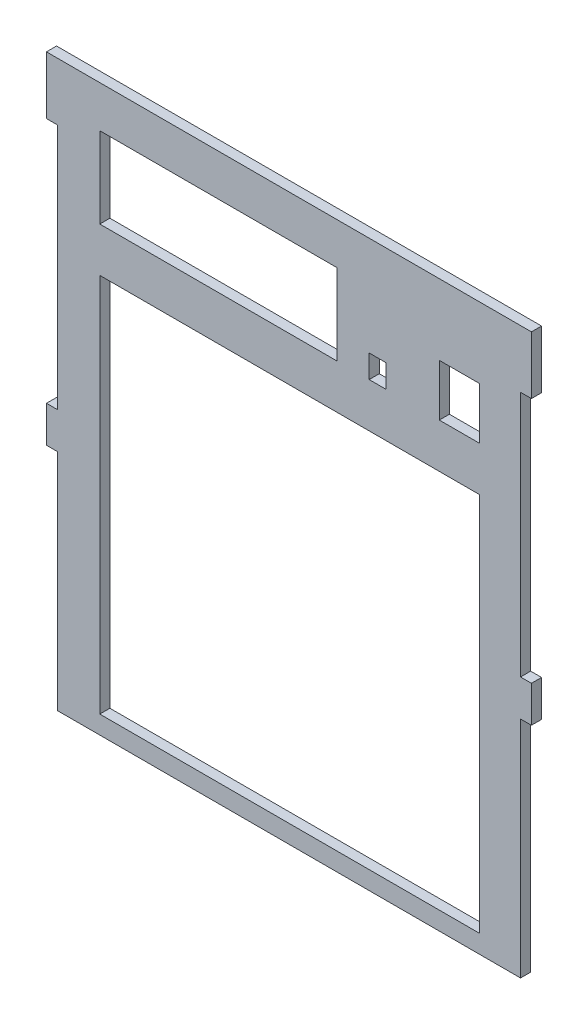
SolidWorks part; units mm, degrees
ref_plane "Front Plane" through (0, 0, 0) normal (0, 0, 1) x (1, 0, 0)
ref_plane "Top Plane" through (0, 0, 0) normal (0, 1, 0) x (1, 0, 0)
ref_plane "Right Plane" through (0, 0, 0) normal (1, 0, 0) x (0, 0, -1)
sketch "Sketch1" plane through (0, 0, 0) normal (0, 0, 1) x (1, 0, 0)
  line L1 (0, 0) -> (152.4, 0)
  line L2 (0, 0) -> (0, 241.3)
  line L3 (0, 241.3) -> (152.4, 241.3)
  line L4 (152.4, 0) -> (152.4, 241.3)
  dimension "D1" = 241.3
  dimension "D2" = 152.4
extrude "Boss-Extrude1" add sketch "Sketch1" along normal blind 3.175
sketch "Sketch2" plane through (0, 0, 3.175) normal (0, 0, 1) x (1, 0, 0)
  line L0 (152.4, 0) -> (152.4, 241.3) construction
  line L1 (152.4, 223.139) -> (148.971, 223.139)
  line L2 (152.4, 223.139) -> (152.4, 54.991)
  line L3 (152.4, 54.991) -> (148.971, 54.991)
  line L4 (148.971, 223.139) -> (148.971, 54.991)
  line L5 (0, 241.3) -> (0, 0) construction
  line L6 (0, 223.139) -> (3.429, 223.139)
  line L7 (0, 223.139) -> (0, 54.991)
  line L8 (0, 54.991) -> (3.429, 54.991)
  line L9 (3.429, 223.139) -> (3.429, 54.991)
  line L10 (152.4, 241.3) -> (0, 241.3) construction
  line L12 (152.4, 0) -> (148.971, 0)
  line L13 (152.4, 0) -> (152.4, 40.386)
  line L14 (152.4, 40.386) -> (148.971, 40.386)
  line L15 (148.971, 0) -> (148.971, 40.386)
  line L16 (0, 0) -> (3.429, 0)
  line L17 (0, 0) -> (0, 40.386)
  line L18 (0, 40.386) -> (3.429, 40.386)
  line L19 (3.429, 0) -> (3.429, 40.386)
  dimension "D1" = 18.161
  dimension "D2" = 14.605
  dimension "D3" = 3.429
  dimension "D4" = 40.386
extrude "Cut-Extrude1" cut sketch "Sketch2" against normal through all
sketch "Sketch3" plane through (0, 0, 3.175) normal (0, 0, 1) x (1, 0, 0)
  line L0 (3.429, 57.15) -> (148.971, 57.15) construction
  line L1 (3.429, 0) -> (148.971, 0) construction
  line L2 (148.971, 223.139) -> (148.971, 54.991) construction
  line L3 (3.429, 54.991) -> (3.429, 223.139) construction
  line L4 (128.016, 57.15) -> (140.716, 57.15)
  line L5 (140.716, 57.15) -> (140.716, 44.45)
  line L6 (140.716, 44.45) -> (128.016, 57.15)
  line L7 (125.7709, 57.15) -> (140.716, 42.2049) construction
  line L8 (125.7709, 42.2049) -> (138.4709, 42.2049)
  line L9 (125.7709, 54.9049) -> (125.7709, 42.2049)
  line L10 (138.4709, 42.2049) -> (125.7709, 54.9049)
  line L11 (108.966, 57.15) -> (121.666, 57.15)
  line L12 (121.666, 44.45) -> (108.966, 57.15)
  line L13 (119.4209, 42.2049) -> (106.7209, 54.9049)
  line L14 (106.7209, 54.9049) -> (106.7209, 42.2049)
  line L15 (106.7209, 42.2049) -> (119.4209, 42.2049)
  line L16 (121.666, 57.15) -> (121.666, 44.45)
  line L17 (89.916, 57.15) -> (102.616, 57.15)
  line L18 (102.616, 44.45) -> (89.916, 57.15)
  line L19 (100.3709, 42.2049) -> (87.6709, 54.9049)
  line L20 (87.6709, 54.9049) -> (87.6709, 42.2049)
  line L21 (87.6709, 42.2049) -> (100.3709, 42.2049)
  line L22 (102.616, 57.15) -> (102.616, 44.45)
  line L23 (70.866, 57.15) -> (83.566, 57.15)
  line L24 (83.566, 44.45) -> (70.866, 57.15)
  line L25 (81.3209, 42.2049) -> (68.6209, 54.9049)
  line L26 (68.6209, 54.9049) -> (68.6209, 42.2049)
  line L27 (68.6209, 42.2049) -> (81.3209, 42.2049)
  line L28 (83.566, 57.15) -> (83.566, 44.45)
  line L29 (51.816, 57.15) -> (64.516, 57.15)
  line L30 (64.516, 44.45) -> (51.816, 57.15)
  line L31 (62.2709, 42.2049) -> (49.5709, 54.9049)
  line L32 (49.5709, 54.9049) -> (49.5709, 42.2049)
  line L33 (49.5709, 42.2049) -> (62.2709, 42.2049)
  line L34 (64.516, 57.15) -> (64.516, 44.45)
  line L35 (32.766, 57.15) -> (45.466, 57.15)
  line L36 (45.466, 44.45) -> (32.766, 57.15)
  line L37 (43.2209, 42.2049) -> (30.5209, 54.9049)
  line L38 (30.5209, 54.9049) -> (30.5209, 42.2049)
  line L39 (30.5209, 42.2049) -> (43.2209, 42.2049)
  line L40 (45.466, 57.15) -> (45.466, 44.45)
  line L41 (13.716, 57.15) -> (26.416, 57.15)
  line L42 (26.416, 44.45) -> (13.716, 57.15)
  line L43 (24.1709, 42.2049) -> (11.4709, 54.9049)
  line L44 (11.4709, 54.9049) -> (11.4709, 42.2049)
  line L45 (11.4709, 42.2049) -> (24.1709, 42.2049)
  line L46 (26.416, 57.15) -> (26.416, 44.45)
  line L47 (128.016, 38.1) -> (140.716, 38.1)
  line L48 (16.764, 188.849) -> (136.144, 188.849)
  line L49 (16.764, 188.849) -> (16.764, 69.469)
  line L50 (16.764, 69.469) -> (136.144, 69.469)
  line L51 (136.144, 188.849) -> (136.144, 69.469)
  line L52 (140.716, 38.1) -> (140.716, 25.4)
  line L53 (140.716, 25.4) -> (128.016, 38.1)
  line L54 (125.7709, 23.1549) -> (138.4709, 23.1549)
  line L55 (125.7709, 35.8549) -> (125.7709, 23.1549)
  line L56 (138.4709, 23.1549) -> (125.7709, 35.8549)
  line L57 (108.966, 38.1) -> (121.666, 38.1)
  line L58 (121.666, 25.4) -> (108.966, 38.1)
  line L59 (119.4209, 23.1549) -> (106.7209, 35.8549)
  line L60 (106.7209, 35.8549) -> (106.7209, 23.1549)
  line L61 (106.7209, 23.1549) -> (119.4209, 23.1549)
  line L62 (121.666, 38.1) -> (121.666, 25.4)
  line L63 (89.916, 38.1) -> (102.616, 38.1)
  line L64 (102.616, 25.4) -> (89.916, 38.1)
  line L65 (100.3709, 23.1549) -> (87.6709, 35.8549)
  line L66 (87.6709, 35.8549) -> (87.6709, 23.1549)
  line L67 (87.6709, 23.1549) -> (100.3709, 23.1549)
  line L68 (102.616, 38.1) -> (102.616, 25.4)
  line L69 (70.866, 38.1) -> (83.566, 38.1)
  line L70 (83.566, 25.4) -> (70.866, 38.1)
  line L71 (81.3209, 23.1549) -> (68.6209, 35.8549)
  line L72 (68.6209, 35.8549) -> (68.6209, 23.1549)
  line L73 (68.6209, 23.1549) -> (81.3209, 23.1549)
  line L74 (83.566, 38.1) -> (83.566, 25.4)
  line L75 (51.816, 38.1) -> (64.516, 38.1)
  line L76 (64.516, 25.4) -> (51.816, 38.1)
  line L77 (62.2709, 23.1549) -> (49.5709, 35.8549)
  line L78 (49.5709, 35.8549) -> (49.5709, 23.1549)
  line L79 (49.5709, 23.1549) -> (62.2709, 23.1549)
  line L80 (64.516, 38.1) -> (64.516, 25.4)
  line L81 (32.766, 38.1) -> (45.466, 38.1)
  line L82 (45.466, 25.4) -> (32.766, 38.1)
  line L83 (43.2209, 23.1549) -> (30.5209, 35.8549)
  line L84 (30.5209, 35.8549) -> (30.5209, 23.1549)
  line L85 (30.5209, 23.1549) -> (43.2209, 23.1549)
  line L86 (45.466, 38.1) -> (45.466, 25.4)
  line L87 (13.716, 38.1) -> (26.416, 38.1)
  line L88 (26.416, 25.4) -> (13.716, 38.1)
  line L89 (24.1709, 23.1549) -> (11.4709, 35.8549)
  line L90 (11.4709, 35.8549) -> (11.4709, 23.1549)
  line L91 (11.4709, 23.1549) -> (24.1709, 23.1549)
  line L92 (26.416, 38.1) -> (26.416, 25.4)
  line L93 (128.016, 19.05) -> (140.716, 19.05)
  line L94 (140.716, 19.05) -> (140.716, 6.35)
  line L95 (140.716, 6.35) -> (128.016, 19.05)
  line L96 (125.7709, 4.1049) -> (138.4709, 4.1049)
  line L97 (125.7709, 16.8049) -> (125.7709, 4.1049)
  line L98 (138.4709, 4.1049) -> (125.7709, 16.8049)
  line L99 (108.966, 19.05) -> (121.666, 19.05)
  line L100 (121.666, 6.35) -> (108.966, 19.05)
  line L101 (119.4209, 4.1049) -> (106.7209, 16.8049)
  line L102 (106.7209, 16.8049) -> (106.7209, 4.1049)
  line L103 (106.7209, 4.1049) -> (119.4209, 4.1049)
  line L104 (121.666, 19.05) -> (121.666, 6.35)
  line L105 (89.916, 19.05) -> (102.616, 19.05)
  line L106 (102.616, 6.35) -> (89.916, 19.05)
  line L107 (100.3709, 4.1049) -> (87.6709, 16.8049)
  line L108 (87.6709, 16.8049) -> (87.6709, 4.1049)
  line L109 (87.6709, 4.1049) -> (100.3709, 4.1049)
  line L110 (102.616, 19.05) -> (102.616, 6.35)
  line L111 (70.866, 19.05) -> (83.566, 19.05)
  line L112 (83.566, 6.35) -> (70.866, 19.05)
  line L113 (81.3209, 4.1049) -> (68.6209, 16.8049)
  line L114 (68.6209, 16.8049) -> (68.6209, 4.1049)
  line L115 (68.6209, 4.1049) -> (81.3209, 4.1049)
  line L116 (83.566, 19.05) -> (83.566, 6.35)
  line L117 (51.816, 19.05) -> (64.516, 19.05)
  line L118 (64.516, 6.35) -> (51.816, 19.05)
  line L119 (62.2709, 4.1049) -> (49.5709, 16.8049)
  line L120 (49.5709, 16.8049) -> (49.5709, 4.1049)
  line L121 (49.5709, 4.1049) -> (62.2709, 4.1049)
  line L122 (64.516, 19.05) -> (64.516, 6.35)
  line L123 (32.766, 19.05) -> (45.466, 19.05)
  line L124 (45.466, 6.35) -> (32.766, 19.05)
  line L125 (43.2209, 4.1049) -> (30.5209, 16.8049)
  line L126 (30.5209, 16.8049) -> (30.5209, 4.1049)
  line L127 (30.5209, 4.1049) -> (43.2209, 4.1049)
  line L128 (45.466, 19.05) -> (45.466, 6.35)
  line L129 (13.716, 19.05) -> (26.416, 19.05)
  line L130 (26.416, 6.35) -> (13.716, 19.05)
  line L131 (24.1709, 4.1049) -> (11.4709, 16.8049)
  line L132 (11.4709, 16.8049) -> (11.4709, 4.1049)
  line L133 (11.4709, 4.1049) -> (24.1709, 4.1049)
  line L134 (26.416, 19.05) -> (26.416, 6.35)
  line L136 (16.764, 228.219) -> (91.3765, 228.219)
  line L137 (16.764, 228.219) -> (16.764, 202.819)
  line L138 (16.764, 202.819) -> (91.3765, 202.819)
  line L139 (91.3765, 228.219) -> (91.3765, 202.819)
  line L148 (123.444, 219.075) -> (136.144, 219.075)
  line L149 (123.444, 219.075) -> (123.444, 202.819)
  line L150 (123.444, 202.819) -> (136.144, 202.819)
  line L151 (136.144, 219.075) -> (136.144, 202.819)
  line L156 (101.4095, 210.058) -> (106.7435, 210.058)
  line L157 (101.4095, 210.058) -> (101.4095, 202.819)
  line L158 (101.4095, 202.819) -> (106.7435, 202.819)
  line L159 (106.7435, 210.058) -> (106.7435, 202.819)
  point P152 (104.0765, 210.058)
  dimension "D1" = 57.15
  dimension "D2" = 12.7
  dimension "D3" = 8.255
  dimension "D4" = 1.5875
  dimension "D6" = 188.849
  dimension "D7" = 119.38
  dimension "D8" = 13.335
  dimension "D10" = 74.6125
  dimension "D11" = 25.4
  dimension "D12" = 16.256
  dimension "D13" = 12.7
  dimension "D15" = 5.334
  dimension "D16" = 7.239
  dimension "D17" = 13.97
  dimension "D18" = 12.7
  dimension "D5" = 7
  dimension "D9" = 3
extrude "Cut-Extrude2" cut sketch "Sketch3" against normal through all
sketch "Sketch4" plane through (0, 0, 3.175) normal (0, 0, 1) x (1, 0, 0)
  line L0 (3.429, 63.754) -> (148.971, 63.754) construction
  line L1 (3.429, 54.991) -> (3.429, 223.139) construction
  line L2 (148.971, 223.139) -> (148.971, 54.991) construction
  line L3 (3.429, 0) -> (148.971, 0) construction
  line L5 (169.3909, 63.754) -> (-15.3067, 63.754)
  line L6 (169.3909, 63.754) -> (169.3909, 0)
  line L7 (169.3909, 0) -> (-15.3067, 0)
  line L8 (-15.3067, 63.754) -> (-15.3067, 0)
  dimension "D1" = 63.754
extrude "Cut-Extrude5" cut sketch "Sketch4" against normal through all
sketch "Sketch5" plane through (0, 0, 3.175) normal (0, 0, 1) x (1, 0, 0)
  line L1 (3.429, 63.754) -> (3.429, 223.139) construction
  line L2 (3.429, 145.669) -> (0, 145.669)
  line L3 (3.429, 145.669) -> (3.429, 134.239)
  line L4 (3.429, 134.239) -> (0, 134.239)
  line L5 (0, 145.669) -> (0, 134.239)
  line L6 (148.971, 223.139) -> (148.971, 63.754) construction
  line L7 (148.971, 145.669) -> (152.4, 145.669)
  line L8 (148.971, 145.669) -> (148.971, 134.239)
  line L9 (148.971, 134.239) -> (152.4, 134.239)
  line L10 (152.4, 145.669) -> (152.4, 134.239)
  line L11 (152.4, 223.139) -> (148.971, 223.139) construction
  line L14 (152.4, 241.3) -> (0, 241.3) construction
  dimension "D1" = 107.061
  dimension "D2" = 11.43
extrude "Boss-Extrude2" add sketch "Sketch5" against normal up to surface (3.175 mm away) up to face at (76.2, 187.833, 0)
